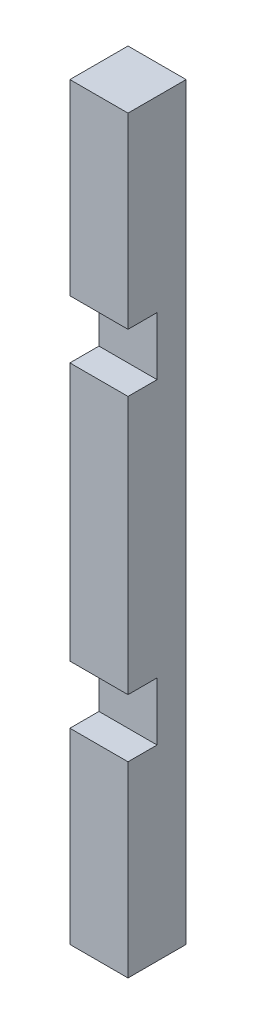
SolidWorks part; units mm, degrees
ref_plane "Front Plane" through (0, 0, 0) normal (0, 0, 1) x (1, 0, 0)
ref_plane "Top Plane" through (0, 0, 0) normal (0, 1, 0) x (1, 0, 0)
ref_plane "Right Plane" through (0, 0, 0) normal (1, 0, 0) x (0, 0, -1)
sketch "Sketch1" plane through (0, 0, 0) normal (0, 1, 0) x (1, 0, 0)
  line L1 (0, 0) -> (90, 0)
  line L2 (0, 0) -> (0, 90)
  line L3 (0, 90) -> (90, 90)
  line L4 (90, 0) -> (90, 90)
  dimension "D1" = 90
  dimension "D2" = 90
extrude "Boss-Extrude1" add sketch "Sketch1" along normal blind 1160
sketch "Sketch3" plane through (0, 0, 0) normal (0, 0, 1) x (1, 0, 0)
  line L0 (0, 1160) -> (0, 0) construction
  line L1 (0, 870) -> (90, 870)
  line L2 (0, 870) -> (0, 780)
  line L3 (0, 780) -> (90, 780)
  line L4 (90, 870) -> (90, 780)
  line L5 (90, 1160) -> (90, 0) construction
  line L6 (0, 1160) -> (90, 1160) construction
  dimension "D1" = 90
  dimension "D2" = 290
extrude "Cut-Extrude1" cut sketch "Sketch3" against normal blind 45
sketch "Sketch4" plane through (0, 0, 0) normal (0, 0, 1) x (1, 0, 0)
  line L0 (90, 780) -> (90, 0) construction
  line L1 (90, 290) -> (0, 290)
  line L2 (90, 290) -> (90, 380)
  line L3 (90, 380) -> (0, 380)
  line L4 (0, 290) -> (0, 380)
  line L5 (0, 780) -> (0, 0) construction
  line L6 (0, 0) -> (90, 0) construction
  dimension "D1" = 90
  dimension "D2" = 290
extrude "Cut-Extrude2" cut sketch "Sketch4" against normal blind 45
